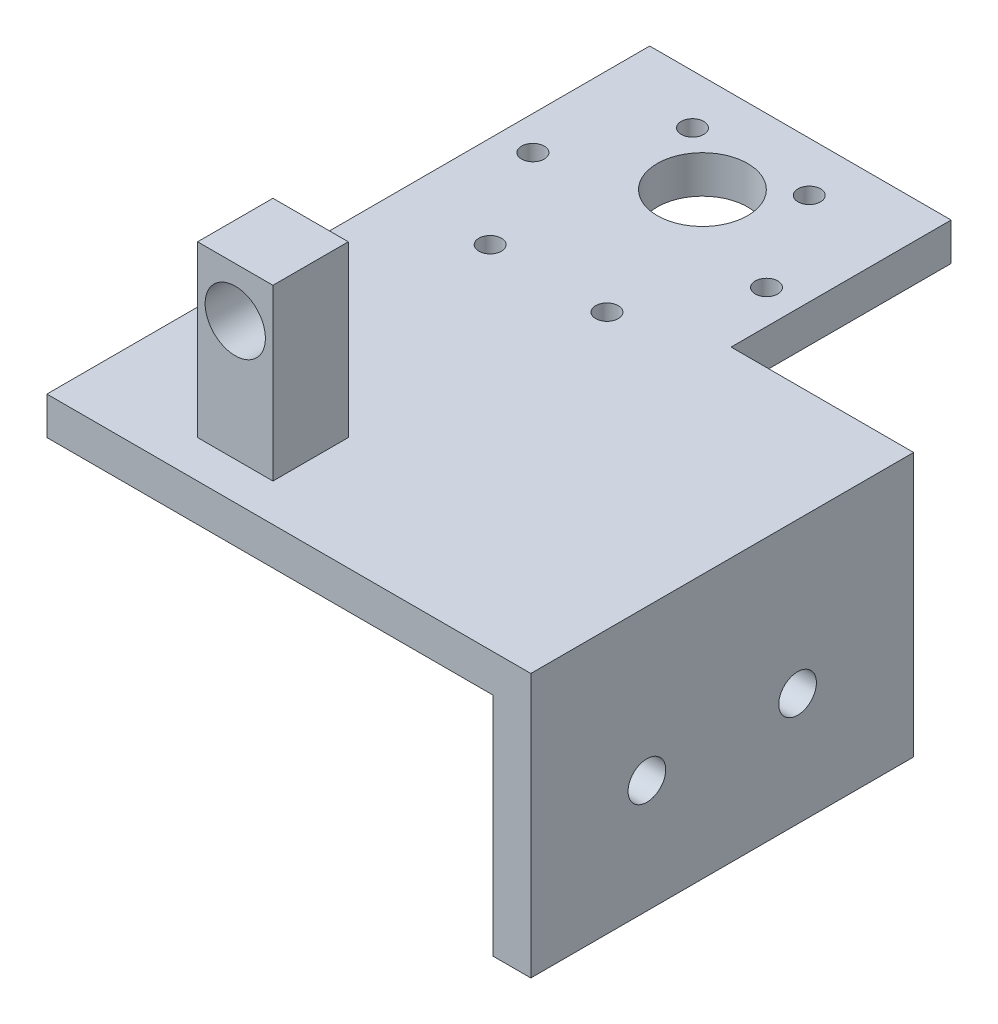
SolidWorks part; units mm, degrees
ref_plane "Front Plane" through (0, 0, 0) normal (0, 0, 1) x (1, 0, 0)
ref_plane "Top Plane" through (0, 0, 0) normal (0, 1, 0) x (1, 0, 0)
ref_plane "Right Plane" through (0, 0, 0) normal (1, 0, 0) x (0, 0, -1)
sketch "Sketch1" plane through (0, 0, 0) normal (0, 1, 0) x (1, 0, 0)
  circle A0 centre (-15.5, 0) radius 1.5
  circle A1 centre (-7.75, 13.4234) radius 1.5
  circle A2 centre (7.75, 13.4234) radius 1.5
  circle A3 centre (15.5, 0) radius 1.5
  circle A4 centre (7.75, -13.4234) radius 1.5
  circle A5 centre (-7.75, -13.4234) radius 1.5
  circle A6 centre (0, 7) radius 6
  point P17 (0, 0)
  dimension "D1" = 3
  dimension "D5" = 12
  dimension "D2" = 15.5
  dimension "D3" = 0
  dimension "D6" = 7
  dimension "D4" = 6
sketch "Sketch3" plane through (0, 0, 0) normal (0, 1, 0) x (1, 0, 0)
  line L1 (-20, 20) -> (20, 20)
  line L2 (-20, 20) -> (-20, -60)
  line L3 (-20, -60) -> (20, -60)
  line L4 (20, 20) -> (20, -60)
  dimension "D1" = 80
  dimension "D2" = 40
  dimension "D3" = 20
  dimension "D4" = 20
extrude "Boss-Extrude1" add sketch "Sketch3" along normal blind 5
extrude "Cut-Extrude3" cut sketch "Sketch1" along normal through all
sketch "Sketch4" plane through (0, 5, 0) normal (0, 1, 0) x (1, 0, 0)
  line L0 (-20, -60) -> (20, -60) construction
  line L1 (5, -45) -> (-5, -45)
  line L2 (5, -45) -> (5, -55)
  line L3 (5, -55) -> (-5, -55)
  line L4 (-5, -45) -> (-5, -55)
  dimension "D1" = 10
  dimension "D2" = 10
  dimension "D3" = 5
  dimension "D4" = 5
extrude "Boss-Extrude2" add sketch "Sketch4" along normal blind 22.5
sketch "Sketch5" plane through (0, 0, 55) normal (0, 0, 1) x (1, 0, 0)
  line L2 (-5, 5) -> (5, 5) construction
  circle A0 centre (0, 20.9) radius 4
  dimension "D1" = 8
  dimension "D2" = 15.9
extrude "Cut-Extrude4" cut sketch "Sketch5" against normal blind 8
sketch "Sketch6" plane through (20, 0, 0) normal (1, 0, 0) x (0, 0, -1)
  line L0 (-60, 0) -> (20, 0) construction
  line L1 (-60, 5) -> (-9.2, 5)
  line L2 (-60, 5) -> (-60, 0)
  line L3 (-60, 0) -> (-9.2, 0)
  line L4 (-9.2, 5) -> (-9.2, 0)
  dimension "D1" = 50.8
extrude "Boss-Extrude3" add sketch "Sketch6" along normal blind 24.225
sketch "Sketch8" plane through (0, 0, 0) normal (0, -1, 0) x (1, 0, 0)
  line L0 (44.225, 9.2) -> (20, 9.2) construction
  line L1 (44.225, 60) -> (39.225, 60)
  line L2 (44.225, 60) -> (44.225, 9.2)
  line L3 (44.225, 9.2) -> (39.225, 9.2)
  line L4 (39.225, 60) -> (39.225, 9.2)
  dimension "D1" = 5
extrude "Boss-Extrude4" add sketch "Sketch8" along normal blind 30
sketch "Sketch9" plane through (44.225, 0, 0) normal (1, 0, 0) x (0, 0, -1)
  line L0 (-9.2, -30) -> (-60, -30) construction
  line L1 (-60, 5) -> (-60, -30) construction
  circle A0 centre (-44.6, -15) radius 2.5
  circle A1 centre (-24.6, -15) radius 2.5
  dimension "D1" = 5
  dimension "D2" = 5
  dimension "D3" = 20
  dimension "D4" = 0
  dimension "D5" = 15
  dimension "D6" = 15.4
extrude "Cut-Extrude5" cut sketch "Sketch9" against normal up to surface (5 mm away) up to face at (39.225, -15, 34.6)
